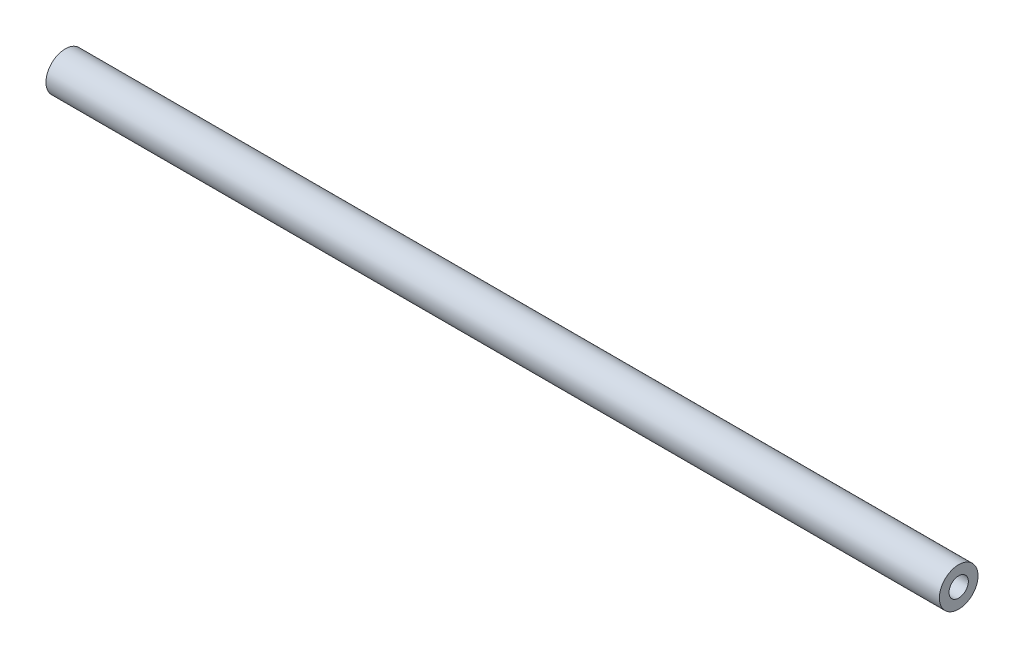
SolidWorks part; units mm, degrees
ref_plane "Front" through (0, 0, 0) normal (0, 0, 1) x (1, 0, 0)
ref_plane "Top" through (0, 0, 0) normal (0, 1, 0) x (1, 0, 0)
ref_plane "Right" through (0, 0, 0) normal (1, 0, 0) x (0, 0, -1)
sketch "草图1" plane through (0, 0, 0) normal (1, 0, 0) x (0, 0, -1)
  circle A0 centre (0, 0) radius 4
  circle A1 centre (0, 0) radius 2
  dimension "D1" = 8
  dimension "D2" = 4
extrude "凸台-拉伸1" add sketch "草图1" along normal blind 185
